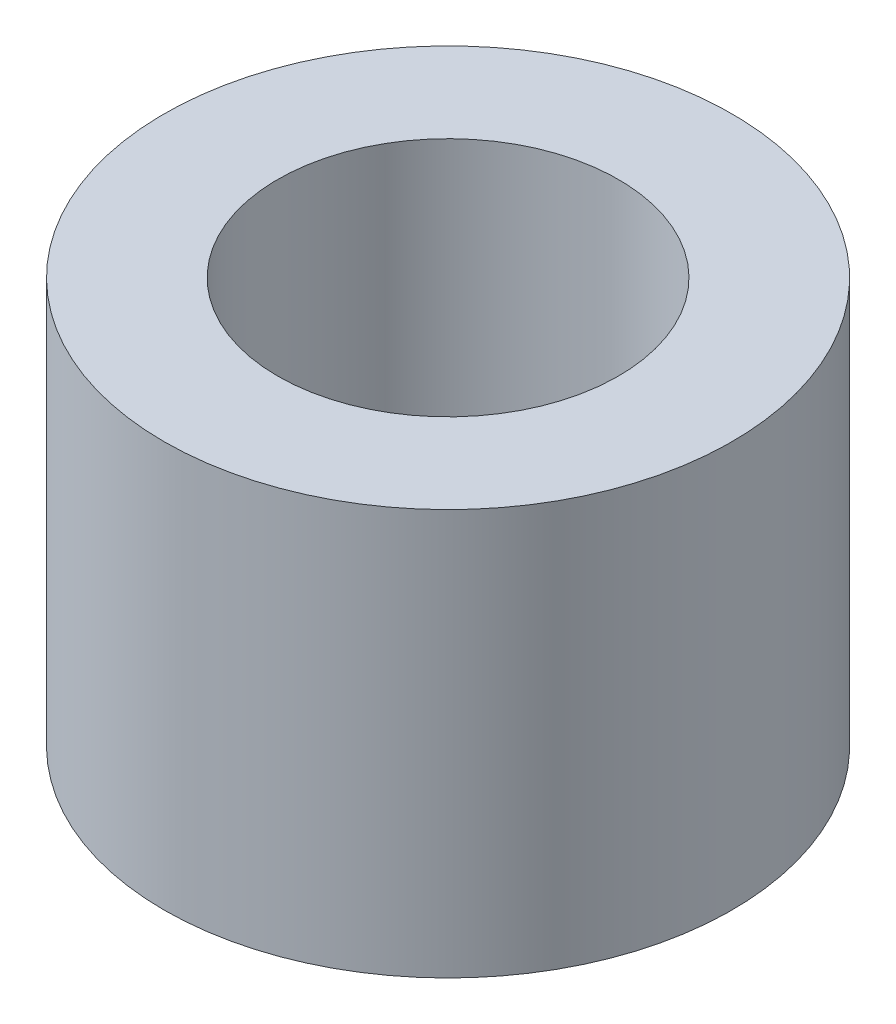
SolidWorks part; units mm, degrees
ref_plane "前视" through (0, 0, 0) normal (0, 0, 1) x (1, 0, 0)
ref_plane "上视" through (0, 0, 0) normal (0, 1, 0) x (1, 0, 0)
ref_plane "右视" through (0, 0, 0) normal (1, 0, 0) x (0, 0, -1)
sketch "草图1" plane through (0, 0, 0) normal (0, 1, 0) x (1, 0, 0)
  circle A0 centre (0, 0) radius 3.5
  circle A1 centre (0, 0) radius 2.1
  dimension "D1" = 7
  dimension "D2" = 4.2
extrude "凸台-拉伸1" add sketch "草图1" along normal blind 5
